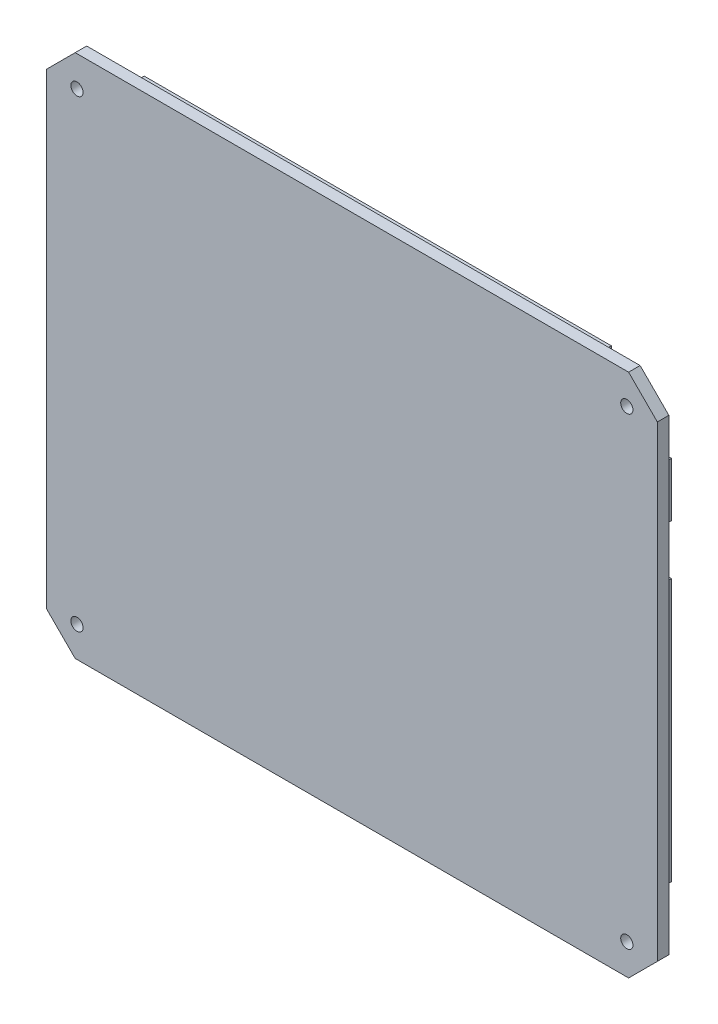
SolidWorks part; units mm, degrees
ref_plane "前视基准面" through (0, 0, 0) normal (0, 0, 1) x (1, 0, 0)
ref_plane "上视基准面" through (0, 0, 0) normal (0, 1, 0) x (1, 0, 0)
ref_plane "右视基准面" through (0, 0, 0) normal (1, 0, 0) x (0, 0, -1)
other "Configuration Table"
sketch "Cover 3.2 - four screw clearances D3.4 profile" plane through (0, 0, 0) normal (0, 0, 1) x (1, 0, 0)
  line L0 (-77, -73) -> (77, -73)
  line L1 (77, -73) -> (85, -65)
  line L2 (85, -65) -> (85, 65)
  line L3 (85, 65) -> (77, 73)
  line L4 (77, 73) -> (-77, 73)
  line L5 (-77, 73) -> (-85, 65)
  line L6 (-85, 65) -> (-85, -65)
  line L7 (-85, -65) -> (-77, -73)
  circle A0 centre (-76.5, -64.5) radius 1.7
  circle A1 centre (-76.5, 64.5) radius 1.7
  circle A2 centre (76.5, -64.5) radius 1.7
  circle A3 centre (76.5, 64.5) radius 1.7
extrude "Cover 3.2 - four screw clearances D3.4" add sketch "Cover 3.2 - four screw clearances D3.4 profile" along normal blind 3.2 from offset 4
sketch "Locating lips - 0.45 wall clearance profile" plane through (0, 0, 0) normal (0, 0, 1) x (1, 0, 0)
  line L0 (-65, -69.75) -> (65, -69.75)
  line L1 (65, -69.75) -> (65, -68.15)
  line L2 (65, -68.15) -> (-65, -68.15)
  line L3 (-65, -68.15) -> (-65, -69.75)
  line L4 (-65, 68.15) -> (65, 68.15)
  line L5 (65, 68.15) -> (65, 69.75)
  line L6 (65, 69.75) -> (-65, 69.75)
  line L7 (-65, 69.75) -> (-65, 68.15)
  line L8 (-81.75, -51) -> (-80.15, -51)
  line L9 (-80.15, -51) -> (-80.15, 19)
  line L10 (-80.15, 19) -> (-81.75, 19)
  line L11 (-81.75, 19) -> (-81.75, -51)
  line L12 (-81.75, 39) -> (-80.15, 39)
  line L13 (-80.15, 39) -> (-80.15, 51)
  line L14 (-80.15, 51) -> (-81.75, 51)
  line L15 (-81.75, 51) -> (-81.75, 39)
  line L16 (80.15, -51) -> (81.75, -51)
  line L17 (81.75, -51) -> (81.75, 22)
  line L18 (81.75, 22) -> (80.15, 22)
  line L19 (80.15, 22) -> (80.15, -51)
  line L20 (80.15, 36) -> (81.75, 36)
  line L21 (81.75, 36) -> (81.75, 51)
  line L22 (81.75, 51) -> (80.15, 51)
  line L23 (80.15, 51) -> (80.15, 36)
extrude "Locating lips - 0.45 wall clearance" add sketch "Locating lips - 0.45 wall clearance profile" along normal blind 4
